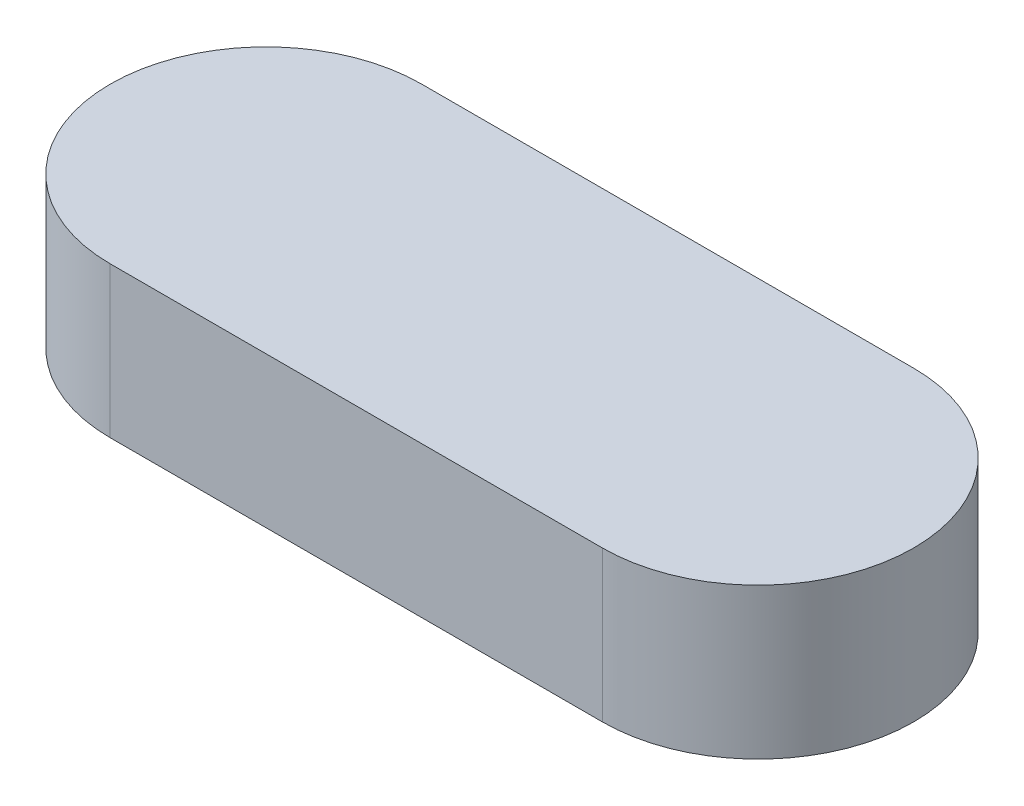
SolidWorks part; units mm, degrees
ref_plane "Front Plane" through (0, 0, 0) normal (0, 0, 1) x (1, 0, 0)
ref_plane "Top Plane" through (0, 0, 0) normal (0, 1, 0) x (1, 0, 0)
ref_plane "Right Plane" through (0, 0, 0) normal (1, 0, 0) x (0, 0, -1)
sketch "Sketch1" plane through (0, 0, 0) normal (0, 1, 0) x (1, 0, 0)
  line L0 (-12.25, 0) -> (12.25, 0) construction
  line L1 (-12.25, 7.75) -> (12.25, 7.75)
  line L2 (-12.25, -7.75) -> (12.25, -7.75)
  arc A0 (-12.25, 7.75) -> (-12.25, -7.75) centre (-12.25, 0) ccw
  arc A1 (12.25, -7.75) -> (12.25, 7.75) centre (12.25, 0) ccw
  point P3 (0, 0)
  dimension "D2" = 7.75
  dimension "D1" = 24.5
extrude "Boss-Extrude1" add sketch "Sketch1" along normal blind 7.5
